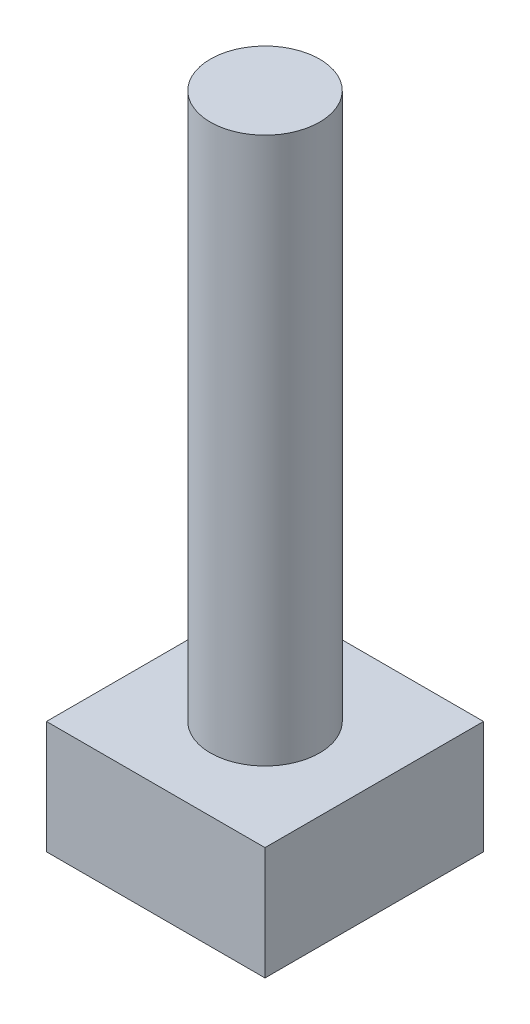
SolidWorks part; units mm, degrees
ref_plane "前视" through (0, 0, 0) normal (0, 0, 1) x (1, 0, 0)
ref_plane "上视" through (0, 0, 0) normal (0, 1, 0) x (1, 0, 0)
ref_plane "右视" through (0, 0, 0) normal (1, 0, 0) x (0, 0, -1)
sketch "草图1" plane through (0, 0, 0) normal (0, 1, 0) x (1, 0, 0)
  line L0 (0, 96.9306) -> (0, -101.3275) construction
  line L1 (-119.7143, 0) -> (134.9034, 0) construction
  line L3 (-3, 3) -> (3, 3)
  line L4 (-3, 3) -> (-3, -3)
  line L5 (-3, -3) -> (3, -3)
  line L6 (3, 3) -> (3, -3)
  dimension "D1" = 6
  dimension "D2" = 6
extrude "拉伸1" add sketch "草图1" along normal blind 3.1
sketch "草图2" plane through (0, 3.1, 0) normal (0, 1, 0) x (-1, 0, 0)
  line L0 (-3, 0) -> (8.7109, 0) construction
  line L1 (-3, 3) -> (-3, -3) construction
  line L2 (0, -7.8518) -> (0, 10.0992) construction
  circle A0 centre (0, 0) radius 1.5
  dimension "D1" = 3
extrude "拉伸2" add sketch "草图2" along normal blind 15
sketch "草图3" plane through (-3, 0, 0) normal (-1, 0, 0) x (0, 0, 1)
  line L0 (0, -6.9925) -> (0, 14.8526) construction
sketch "草图4" plane through (0, 18.1, 0) normal (0, 1, 0) x (-1, 0, 0)
  line L0 (0, -4.1469) -> (0, 4.9476) construction
  line L1 (-3.9082, 0) -> (5.1305, 0) construction
sketch "草图5" plane through (0, 0, 0) normal (0, -1, 0) x (1, 0, 0)
  line L0 (-4.4583, 0) -> (4.1341, 0) construction
  line L1 (0, 4.6756) -> (0, -4.3899) construction
